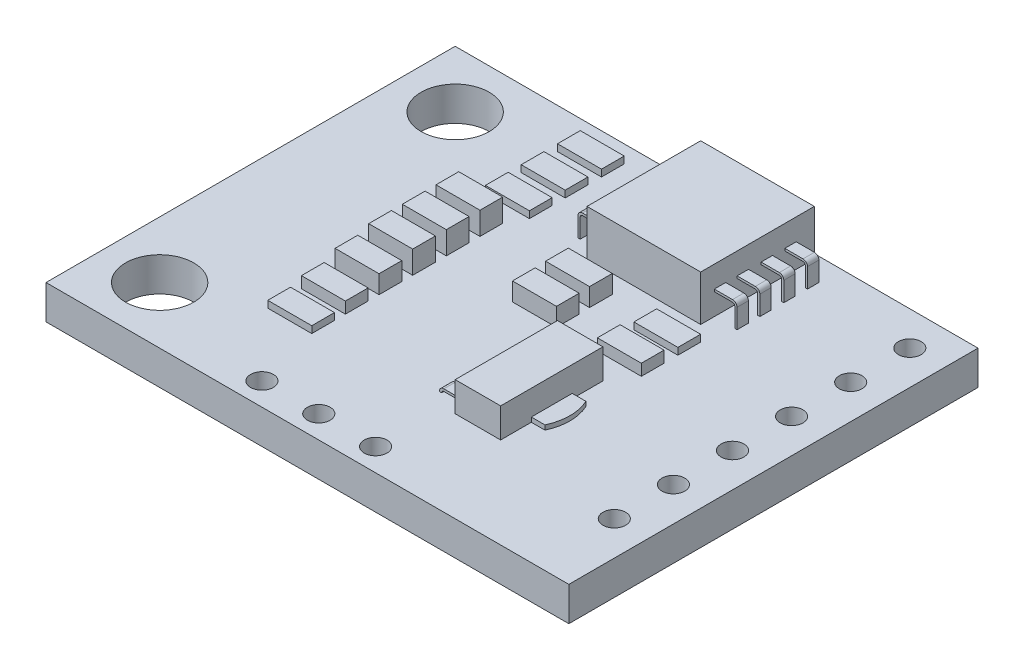
SolidWorks part; units mm, degrees
ref_plane "Plano frontal" through (0, 0, 0) normal (0, 0, 1) x (1, 0, 0)
ref_plane "Plano superior" through (0, 0, 0) normal (0, 1, 0) x (1, 0, 0)
ref_plane "Plano direito" through (0, 0, 0) normal (1, 0, 0) x (0, 0, -1)
sketch "Esboço1" plane through (0, 0, 0) normal (0, 1, 0) x (1, 0, 0)
  line L0 (-13.9391, 0) -> (15.2769, 0) construction
  line L1 (-11.5, -9) -> (11.5, -9)
  line L2 (-11.5, -9) -> (-11.5, 9)
  line L3 (-11.5, 9) -> (11.5, 9)
  line L4 (11.5, -9) -> (11.5, 9)
  line L5 (-11.5, -9) -> (11.5, 9) construction
  line L6 (-11.5, 9) -> (11.5, -9) construction
  line L7 (0, 11.5695) -> (0, -11.5756) construction
  point P0 (0, 0)
  dimension "D1" = 23
  dimension "D2" = 18
extrude "PCB" add sketch "Esboço1" against normal blind 1.5
sketch "Esboço7" plane through (-11.5, 0, 9) normal (0, 1, 0) x (1, 0, 0)
  line L0 (0, 18) -> (0, 0) construction
  line L1 (8.5, 1) -> (13.5, 1) construction
  line L2 (0, 18) -> (0, 0) construction
  line L4 (0, 0) -> (23, 0) construction
  line L5 (8.5, 1.5) -> (13.5, 1.5) construction
  circle A0 centre (2.5, 2.5) radius 1.5
  circle A1 centre (2.5, 15.5) radius 1.5
  circle A2 centre (8.5, 1) radius 0.5
  circle A3 centre (11, 1) radius 0.5
  circle A4 centre (21.5, 16.5) radius 0.5
  circle A5 centre (21.5, 13.9) radius 0.5
  circle A6 centre (21.5, 11.3) radius 0.5
  circle A7 centre (21.5, 8.7) radius 0.5
  circle A8 centre (21.5, 6.1) radius 0.5
  circle A9 centre (21.5, 3.5) radius 0.5
  circle A10 centre (13.5, 1) radius 0.5
  dimension "D1" = 8.5
  dimension "D3" = 21.5
  dimension "D2" = 13.5
  dimension "D4" = 16.5
  dimension "D5" = 2.6
  dimension "D6" = 3.5
extrude "Furos" cut sketch "Esboço7" against normal through all
sketch "Labels" plane through (0, 0, 0) normal (0, 1, 0) x (1, 0, 0)
  line L0 (9.4, -4.734) -> (9.4, -6.3649) construction
  line L1 (-3.7496, -7.4) -> (-2.25, -7.4) construction
  line L2 (9.4, -2.1528) -> (9.4, -3.9588) construction
  line L3 (9.4, -0.9455) -> (9.4, 0.8647) construction
  line L4 (-1.8523, -7.4) -> (0.6571, -7.4) construction
  line L5 (9.4, 1.6501) -> (9.4, 3.3607) construction
  line L6 (9.4, 4.2004) -> (9.4, 5.8231) construction
  line L7 (0.869, -7.4) -> (3.2469, -7.4) construction
  line L8 (9.4, 6.8154) -> (9.4, 8.6677) construction
  circle A1 centre (10, -5.5) radius 0.5 construction
  circle A2 centre (2, -8) radius 0.5 construction
  text T0 "5V" font "Adobe Heiti Std R" height 1
  text T1 "GND" font "Adobe Heiti Std R" height 1
  text T2 "VIN" font "Adobe Heiti Std R" height 1
  text T3 "P0" font "Adobe Heiti Std R" height 1
  text T4 "P1" font "Adobe Heiti Std R" height 1
  text T5 "P2" font "Adobe Heiti Std R" height 1
  text T6 "P3" font "Adobe Heiti Std R" height 1
  text T7 "P4" font "Century Gothic" height 1
  text T8 "P5" font "Adobe Heiti Std R" height 1
  dimension "D1" = 0.6
  dimension "D2" = 0.6
sketch "Esboço11" plane through (0, 0, 0) normal (0, 1, 0) x (1, 0, 0)
  line L0 (-11.5, 9) -> (-11.5, -9) construction
  line L1 (-0.5, 3.8) -> (4.5, 3.8)
  line L2 (-0.5, 3.8) -> (-0.5, 8.8)
  line L3 (-0.5, 8.8) -> (4.5, 8.8)
  line L4 (4.5, 3.8) -> (4.5, 8.8)
  line L5 (-11.5, -9) -> (11.5, -9) construction
  dimension "D1" = 11
  dimension "D2" = 12.8
  dimension "D3" = 5
  dimension "D4" = 5
extrude "CHIP" add sketch "Esboço11" along normal blind 2
sketch "Esboço12" plane through (0, 0, 0) normal (0, 1, 0) x (1, 0, 0)
  line L1 (2.5, -5) -> (4.5, -5)
  line L2 (2.5, -5) -> (2.5, -0.5)
  line L3 (2.5, -0.5) -> (4.5, -0.5)
  line L4 (4.5, -5) -> (4.5, -0.5)
  line L5 (4.5, 3.8) -> (4.5, 8.8) construction
  line L7 (-11.5, -9) -> (11.5, -9) construction
  dimension "D1" = 4.5
  dimension "D2" = 2
  dimension "D3" = 4
extrude "Regulador tensao" add sketch "Esboço12" along normal blind 1.3
sketch "Esboço13" plane through (0, 0, 0) normal (0, 1, 0) x (1, 0, 0)
  line L0 (-3.7091, 2.3) -> (-3.7091, 1.82) construction
  line L13 (-5.644, -0.66) -> (-3.7091, -0.66)
  line L14 (-5.644, -0.66) -> (-5.644, 0.34)
  line L15 (-5.644, 0.34) -> (-3.7091, 0.34)
  line L16 (-3.7091, -0.66) -> (-3.7091, 0.34)
  line L17 (-5.644, 0.82) -> (-3.7091, 0.82)
  line L18 (-5.644, 0.82) -> (-5.644, 1.82)
  line L19 (-5.644, 1.82) -> (-3.7091, 1.82)
  line L20 (-3.7091, 0.82) -> (-3.7091, 1.82)
  line L21 (-5.644, 2.3) -> (-3.7091, 2.3)
  line L22 (-5.644, 2.3) -> (-5.644, 3.3)
  line L23 (-5.644, 3.3) -> (-3.7091, 3.3)
  line L24 (-3.7091, 2.3) -> (-3.7091, 3.3)
  line L25 (-3.7091, 0.82) -> (-3.7091, 0.34) construction
  line L29 (-11.5, -9) -> (11.5, -9) construction
  dimension "D1" = 0.48
  dimension "D2" = 1
  dimension "D3" = 12.3
extrude "Resistores 1" add sketch "Esboço13" along normal blind 1
sketch "Esboço14" plane through (0, 0, 0) normal (0, 1, 0) x (1, 0, 0)
  line L0 (-3.7091, -0.66) -> (-3.7091, -1.14) construction
  line L1 (-5.644, -1.14) -> (-3.7091, -1.14)
  line L2 (-5.644, -1.14) -> (-5.644, -2.14)
  line L3 (-5.644, -2.14) -> (-3.7091, -2.14)
  line L4 (-3.7091, -1.14) -> (-3.7091, -2.14)
  line L13 (-5.644, -0.66) -> (-3.7091, -0.66) construction
  line L14 (-0.5233, 3) -> (1.4116, 3)
  line L15 (-0.5233, 3) -> (-0.5233, 2)
  line L16 (-0.5233, 2) -> (1.4116, 2)
  line L17 (1.4116, 3) -> (1.4116, 2)
  line L18 (-0.5, 1.52) -> (1.4349, 1.52)
  line L19 (-0.5, 1.52) -> (-0.5, 0.52)
  line L20 (-0.5, 0.52) -> (1.4349, 0.52)
  line L21 (1.4349, 1.52) -> (1.4349, 0.52)
  line L22 (-11.5, 9) -> (-11.5, -9) construction
  line L24 (-0.5, 8.8) -> (-0.5, 3.8) construction
  line L25 (-11.5, -9) -> (11.5, -9) construction
  dimension "D1" = 0.48
  dimension "D2" = 1
  dimension "D3" = 10.9767
  dimension "D4" = 0.48
  dimension "D5" = 12
  dimension "D6" = 1
extrude "Resistores 2" add sketch "Esboço14" along normal blind 0.8
sketch "Esboço16" plane through (0, 0, 0) normal (0, 1, 0) x (1, 0, 0)
  line L0 (-5.644, -2.62) -> (-3.7091, -2.62)
  line L1 (-5.644, -2.62) -> (-5.644, -3.62)
  line L2 (-5.644, -3.62) -> (-3.7091, -3.62)
  line L3 (-3.7091, -2.62) -> (-3.7091, -3.62)
  line L4 (-5.644, -1.14) -> (-5.644, -2.14) construction
  line L5 (-3.7091, -2.14) -> (-3.7091, -1.14) construction
  line L6 (-5.644, -2.14) -> (-3.7091, -2.14) construction
  line L7 (3.2349, 1.52) -> (5.1699, 1.52)
  line L8 (3.2349, 1.52) -> (3.2349, 0.52)
  line L9 (3.2349, 0.52) -> (5.1699, 0.52)
  line L10 (5.1699, 1.52) -> (5.1699, 0.52)
  line L11 (1.4349, 0.52) -> (1.4349, 1.52) construction
  line L14 (-0.5, 0.52) -> (1.4349, 0.52) construction
  dimension "D1" = 0.48
  dimension "D2" = 1
  dimension "D3" = 1.8
  dimension "D4" = 1
extrude "LEDs" add sketch "Esboço16" along normal blind 0.5
sketch "Esboço17" plane through (0, 0, 0) normal (0, 1, 0) x (1, 0, 0)
  line L0 (-5.644, -4.1) -> (-3.7091, -4.1)
  line L1 (-5.644, -4.1) -> (-5.644, -5.1)
  line L2 (-5.644, -5.1) -> (-3.7091, -5.1)
  line L3 (-3.7091, -4.1) -> (-3.7091, -5.1)
  line L4 (-5.644, -2.62) -> (-5.644, -3.62) construction
  line L5 (-3.7091, -3.62) -> (-3.7091, -2.62) construction
  line L6 (3.2349, 3.1283) -> (5.1699, 3.1283)
  line L7 (3.2349, 3.1283) -> (3.2349, 2.1283)
  line L8 (3.2349, 2.1283) -> (5.1699, 2.1283)
  line L9 (5.1699, 3.1283) -> (5.1699, 2.1283)
  line L14 (-5.2349, 8.2374) -> (-3.3, 8.2374)
  line L15 (-5.2349, 8.2374) -> (-5.2349, 7.2374)
  line L16 (-5.2349, 7.2374) -> (-3.3, 7.2374)
  line L17 (-3.3, 8.2374) -> (-3.3, 7.2374)
  line L18 (-5.2349, 6.6401) -> (-3.3, 6.6401)
  line L19 (-5.2349, 6.6401) -> (-5.2349, 5.6401)
  line L20 (-5.2349, 5.6401) -> (-3.3, 5.6401)
  line L21 (-3.3, 6.6401) -> (-3.3, 5.6401)
  line L22 (-5.2349, 5.066) -> (-3.3, 5.066)
  line L23 (-5.2349, 5.066) -> (-5.2349, 4.066)
  line L24 (-5.2349, 4.066) -> (-3.3, 4.066)
  line L25 (-3.3, 5.066) -> (-3.3, 4.066)
  line L27 (-11.5, 9) -> (-11.5, -9) construction
  line L28 (3.2349, 1.52) -> (3.2349, 0.52) construction
  line L29 (5.1699, 1.52) -> (3.2349, 1.52) construction
  dimension "D1" = 1
  dimension "D2" = 0.48
  dimension "D4" = 8.2
extrude "Resistores 3" add sketch "Esboço17" along normal blind 0.3
sketch "Esboço18" plane through (4.5, 0, 0) normal (1, 0, 0) x (0, 0, -1)
  line L1 (4.4, 1.05) -> (4.9, 1.05)
  line L2 (4.4, 1.05) -> (4.4, 0.95)
  line L3 (4.4, 0.95) -> (4.9, 0.95)
  line L4 (4.9, 1.05) -> (4.9, 0.95)
  line L7 (3.8, 2) -> (3.8, 0) construction
  line L8 (5.4039, 1.05) -> (5.9039, 1.05)
  line L9 (5.4039, 1.05) -> (5.4039, 0.95)
  line L10 (5.4039, 0.95) -> (5.9039, 0.95)
  line L11 (5.9039, 1.05) -> (5.9039, 0.95)
  line L12 (6.4586, 1.05) -> (6.9586, 1.05)
  line L13 (6.4586, 1.05) -> (6.4586, 0.95)
  line L14 (6.4586, 0.95) -> (6.9586, 0.95)
  line L15 (6.9586, 1.05) -> (6.9586, 0.95)
  line L16 (7.5023, 1.05) -> (8.0023, 1.05)
  line L17 (7.5023, 1.05) -> (7.5023, 0.95)
  line L18 (7.5023, 0.95) -> (8.0023, 0.95)
  line L19 (8.0023, 1.05) -> (8.0023, 0.95)
  line L21 (3.8, 2) -> (8.8, 2) construction
  line L23 (3.8, 0) -> (8.8, 0) construction
  dimension "D1" = 0.5
  dimension "D2" = 0.6
  dimension "D3" = 0.95
  dimension "D4" = 0.95
extrude "Conectores CHIP 1" add sketch "Esboço18" along normal blind 0.8
sketch "Esboço20" plane through (0, 0, -4.4) normal (0, 0, 1) x (1, 0, 0)
  line L0 (5.3, 0.95) -> (5.3, 1.05)
  line L1 (5.4, 0.85) -> (5.4, 0)
  line L2 (5.3, 0.95) -> (5.3, 0.75) construction
  line L3 (5.2, 0.85) -> (5.4, 0.85) construction
  line L4 (9.9, 0) -> (-9.9, 0) construction
  line L5 (5.4, 0) -> (5.4999, 0)
  line L6 (5.4999, 0) -> (5.4999, 0.8551)
  circle A2 centre (5.3, 0.85) radius 0.1 construction
  arc A3 (5.3, 0.95) -> (5.4, 0.85) centre (5.3, 0.85) cw
  arc A4 (5.3, 1.05) -> (5.4999, 0.8551) centre (5.3, 0.85) cw
extrude "Conectores CHIP 2" add sketch "Esboço20" against normal up to vertex
sketch "Esboço21" plane through (0, 0, -5.4039) normal (0, 0, 1) x (1, 0, 0)
  line L0 (5.3, 0.95) -> (5.3, 1.05)
  line L1 (5.4, 0.85) -> (5.4, 0)
  line L2 (5.3, 0.95) -> (5.3, 0.75) construction
  line L3 (5.2, 0.85) -> (5.4, 0.85) construction
  line L4 (5.4, 0) -> (5.4999, 0)
  line L5 (5.4999, 0) -> (5.4999, 0.8551)
  circle A0 centre (5.3, 0.85) radius 0.1 construction
  arc A1 (5.3, 0.95) -> (5.4, 0.85) centre (5.3, 0.85) cw
  arc A2 (5.3, 1.05) -> (5.4999, 0.8551) centre (5.3, 0.85) cw
extrude "Conectores CHIP 3" add sketch "Esboço21" against normal up to vertex
sketch "Esboço22" plane through (0, 0, -6.4586) normal (0, 0, 1) x (1, 0, 0)
  line L0 (5.3, 0.95) -> (5.3, 1.05)
  line L1 (5.4, 0.85) -> (5.4, 0)
  line L2 (5.3, 0.95) -> (5.3, 0.75) construction
  line L3 (5.2, 0.85) -> (5.4, 0.85) construction
  line L4 (5.4, 0) -> (5.4999, 0)
  line L5 (5.4999, 0) -> (5.4999, 0.8551)
  circle A0 centre (5.3, 0.85) radius 0.1 construction
  arc A1 (5.3, 0.95) -> (5.4, 0.85) centre (5.3, 0.85) cw
  arc A2 (5.3, 1.05) -> (5.4999, 0.8551) centre (5.3, 0.85) cw
extrude "Conectores CHIP 4" add sketch "Esboço22" against normal up to vertex
sketch "Esboço23" plane through (0, 0, -7.5023) normal (0, 0, 1) x (1, 0, 0)
  line L0 (5.3, 0.95) -> (5.3, 1.05)
  line L1 (5.4, 0.85) -> (5.4, 0)
  line L2 (5.3, 0.95) -> (5.3, 0.75) construction
  line L3 (5.2, 0.85) -> (5.4, 0.85) construction
  line L4 (5.4, 0) -> (5.4999, 0)
  line L5 (5.4999, 0) -> (5.4999, 0.8551)
  circle A0 centre (5.3, 0.85) radius 0.1 construction
  arc A1 (5.3, 0.95) -> (5.4, 0.85) centre (5.3, 0.85) cw
  arc A2 (5.3, 1.05) -> (5.4999, 0.8551) centre (5.3, 0.85) cw
extrude "Conectores CHIP 5" add sketch "Esboço23" against normal up to vertex
sketch "Esboço24" plane through (-0.5, 0, 0) normal (-1, 0, 0) x (0, 0, 1)
  line L0 (-4.4, 0.95) -> (-4.9, 0.95) construction
  line L1 (-8.0023, 0.95) -> (-7.5023, 0.95)
  line L2 (-8.0023, 0.95) -> (-8.0023, 1.05)
  line L3 (-8.0023, 1.05) -> (-7.5023, 1.05)
  line L4 (-7.5023, 0.95) -> (-7.5023, 1.05)
  line L5 (-6.9586, 0.95) -> (-6.4586, 0.95)
  line L6 (-6.9586, 0.95) -> (-6.9586, 1.05)
  line L7 (-6.9586, 1.05) -> (-6.4586, 1.05)
  line L8 (-6.4586, 0.95) -> (-6.4586, 1.05)
  line L9 (-5.9039, 0.95) -> (-5.4039, 0.95)
  line L10 (-5.9039, 0.95) -> (-5.9039, 1.05)
  line L11 (-5.9039, 1.05) -> (-5.4039, 1.05)
  line L12 (-5.4039, 0.95) -> (-5.4039, 1.05)
  line L13 (-4.9, 0.95) -> (-4.4, 0.95)
  line L14 (-4.9, 0.95) -> (-4.9, 1.05)
  line L15 (-4.9, 1.05) -> (-4.4, 1.05)
  line L16 (-4.4, 0.95) -> (-4.4, 1.05)
  line L17 (-4.9, 0.95) -> (-4.9, 1.05) construction
  line L18 (-5.4039, 0.95) -> (-5.9039, 0.95) construction
  line L19 (-5.9039, 0.95) -> (-5.9039, 1.05) construction
  line L20 (-6.9586, 0.95) -> (-6.9586, 1.05) construction
  line L21 (-6.4586, 0.95) -> (-6.9586, 0.95) construction
  line L22 (-8.0023, 0.95) -> (-8.0023, 1.05) construction
  line L23 (-7.5023, 0.95) -> (-8.0023, 0.95) construction
extrude "Conectores CHIP 6" add sketch "Esboço24" along normal blind 0.8
sketch "Esboço25" plane through (0, 0, -8.0023) normal (0, 0, -1) x (-1, 0, 0)
  line L0 (1.3, 0.95) -> (1.3, 1.05)
  line L1 (1.4, 0.85) -> (1.4, 0)
  line L2 (1.3, 0.95) -> (1.3, 0.75) construction
  line L3 (1.2, 0.85) -> (1.4, 0.85) construction
  line L4 (1.4, 0) -> (1.4999, 0)
  line L5 (1.4999, 0) -> (1.4999, 0.8551)
  circle A0 centre (1.3, 0.85) radius 0.1 construction
  arc A1 (1.3, 0.95) -> (1.4, 0.85) centre (1.3, 0.85) cw
  arc A2 (1.3, 1.05) -> (1.4999, 0.8551) centre (1.3, 0.85) cw
extrude "Conectores CHIP 7" add sketch "Esboço25" against normal up to vertex
sketch "Esboço26" plane through (0, 0, -6.9586) normal (0, 0, -1) x (-1, 0, 0)
  line L0 (1.3, 0.95) -> (1.3, 1.05)
  line L1 (1.4, 0.85) -> (1.4, 0)
  line L2 (1.3, 0.95) -> (1.3, 0.75) construction
  line L3 (1.2, 0.85) -> (1.4, 0.85) construction
  line L4 (1.4, 0) -> (1.4999, 0)
  line L5 (1.4999, 0) -> (1.4999, 0.8551)
  circle A0 centre (1.3, 0.85) radius 0.1 construction
  arc A1 (1.3, 0.95) -> (1.4, 0.85) centre (1.3, 0.85) cw
  arc A2 (1.3, 1.05) -> (1.4999, 0.8551) centre (1.3, 0.85) cw
extrude "Conectores CHIP 8" add sketch "Esboço26" against normal up to vertex
sketch "Esboço27" plane through (0, 0, -5.9039) normal (0, 0, -1) x (-1, 0, 0)
  line L0 (1.3, 0.95) -> (1.3, 1.05)
  line L1 (1.4, 0.85) -> (1.4, 0)
  line L2 (1.3, 0.95) -> (1.3, 0.75) construction
  line L3 (1.2, 0.85) -> (1.4, 0.85) construction
  line L4 (1.4, 0) -> (1.4999, 0)
  line L5 (1.4999, 0) -> (1.4999, 0.8551)
  circle A0 centre (1.3, 0.85) radius 0.1 construction
  arc A1 (1.3, 0.95) -> (1.4, 0.85) centre (1.3, 0.85) cw
  arc A2 (1.3, 1.05) -> (1.4999, 0.8551) centre (1.3, 0.85) cw
extrude "Conectores CHIP 9" add sketch "Esboço27" against normal up to vertex
sketch "Esboço28" plane through (0, 0, -4.9) normal (0, 0, -1) x (-1, 0, 0)
  line L0 (1.3, 0.95) -> (1.3, 1.05)
  line L1 (1.4, 0.85) -> (1.4, 0)
  line L2 (1.3, 0.95) -> (1.3, 0.75) construction
  line L3 (1.2, 0.85) -> (1.4, 0.85) construction
  line L4 (1.4, 0) -> (1.4999, 0)
  line L5 (1.4999, 0) -> (1.4999, 0.8551)
  circle A0 centre (1.3, 0.85) radius 0.1 construction
  arc A1 (1.3, 0.95) -> (1.4, 0.85) centre (1.3, 0.85) cw
  arc A2 (1.3, 1.05) -> (1.4999, 0.8551) centre (1.3, 0.85) cw
extrude "Conectores CHIP 10" add sketch "Esboço28" against normal up to vertex
sketch "Esboço29" plane through (2.5, 0, 0) normal (-1, 0, 0) x (0, 0, 1)
  line L1 (1, 0.1) -> (1.5, 0.1)
  line L2 (1, 0.1) -> (1, 0.2)
  line L3 (1, 0.2) -> (1.5, 0.2)
  line L4 (1.5, 0.1) -> (1.5, 0.2)
  line L5 (2.5, 0.1) -> (3, 0.1)
  line L6 (2.5, 0.1) -> (2.5, 0.2)
  line L7 (2.5, 0.2) -> (3, 0.2)
  line L8 (3, 0.1) -> (3, 0.2)
  line L9 (4, 0.1) -> (4.5, 0.1)
  line L10 (4, 0.1) -> (4, 0.2)
  line L11 (4, 0.2) -> (4.5, 0.2)
  line L12 (4.5, 0.1) -> (4.5, 0.2)
  line L14 (0.5, 1.3) -> (5, 1.3) construction
  line L15 (2.75, 1.3) -> (2.75, 0) construction
  line L16 (0.5, 0) -> (5, 0) construction
  line L17 (0.5, 1.3) -> (0.5, 0) construction
  line L18 (5, 1.3) -> (5, 0) construction
  point P18 (2.75, 0.2)
  dimension "D1" = 0.1
  dimension "D2" = 0.5
  dimension "D3" = 0.5
  dimension "D4" = 0.5
  dimension "D5" = 0.1
extrude "Conectores regulador tensao 1" add sketch "Esboço29" along normal blind 1
sketch "Esboço31" plane through (0, 0, 4.5) normal (0, 0, 1) x (1, 0, 0)
  line L0 (1.5, 0.2) -> (1.5, 0.1)
  line L1 (0.869, 0) -> (3.2469, 0) construction
  line L2 (1.3, 0) -> (1.4, 0)
  arc A0 (1.5, 0.1) -> (1.4, 0) centre (1.5, 0) ccw
  arc A1 (1.5, 0.2) -> (1.3, 0) centre (1.5, 0) ccw
extrude "Conectores regulador tensao 2" add sketch "Esboço31" against normal up to vertex
sketch "Esboço32" plane through (0, 0, 3) normal (0, 0, 1) x (1, 0, 0)
  line L0 (1.5, 0.2) -> (1.5, 0.1)
  line L1 (1.3, 0) -> (1.4, 0)
  arc A0 (1.5, 0.1) -> (1.4, 0) centre (1.5, 0) ccw
  arc A1 (1.5, 0.2) -> (1.3, 0) centre (1.5, 0) ccw
extrude "Conectores regulador tensao 3" add sketch "Esboço32" against normal up to vertex
sketch "Esboço33" plane through (0, 0, 1.5) normal (0, 0, 1) x (1, 0, 0)
  line L0 (1.5, 0.2) -> (1.5, 0.1)
  line L1 (1.3, 0) -> (1.4, 0)
  arc A0 (1.5, 0.1) -> (1.4, 0) centre (1.5, 0) ccw
  arc A1 (1.5, 0.2) -> (1.3, 0) centre (1.5, 0) ccw
extrude "Conectores regulador tensao 4" add sketch "Esboço33" against normal up to vertex
sketch "Esboço37" plane through (0, 0, 0) normal (0, 1, 0) x (1, 0, 0)
  line L0 (4.5, -5) -> (4.5, -0.5) construction
  line L1 (4.5, -1.85) -> (5.1, -1.85)
  line L2 (4.5, -1.85) -> (4.5, -3.65)
  line L3 (4.5, -3.65) -> (5.1, -3.65)
  line L5 (5.3, -1.7584) -> (5.3, -3.7274) construction
  arc A0 (5.1, -1.85) -> (5.1, -3.65) centre (3.175, -2.75) cw
  point P6 (4.5, -2.75)
  point P7 (4.5, -2.75)
  dimension "D1" = 0.6
  dimension "D2" = 1.8
  dimension "D3" = 0.2
extrude "Conectores regulador tensao 5" add sketch "Esboço37" along normal blind 0.2
